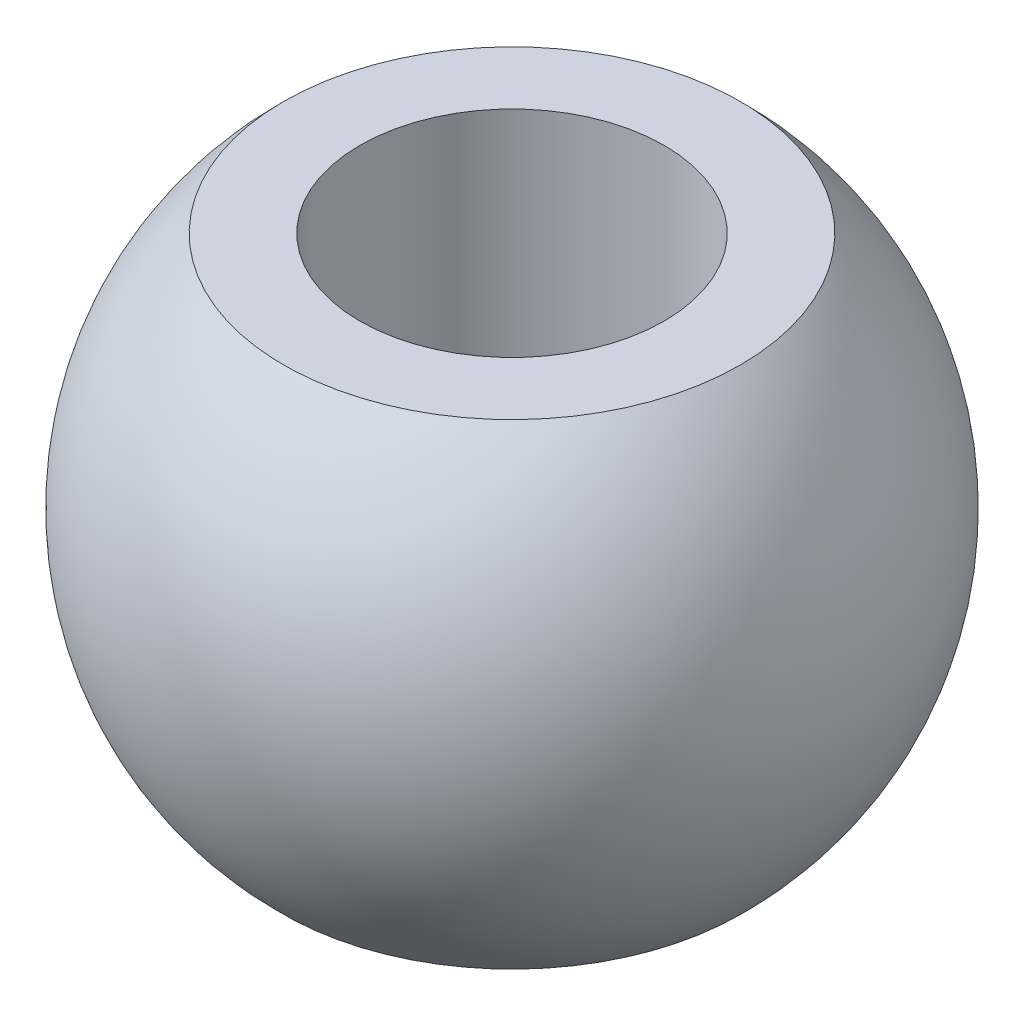
SolidWorks part; units mm, degrees
ref_plane "前视基准面" through (0, 0, 0) normal (0, 0, 1) x (1, 0, 0)
ref_plane "上视基准面" through (0, 0, 0) normal (0, 1, 0) x (1, 0, 0)
ref_plane "右视基准面" through (0, 0, 0) normal (1, 0, 0) x (0, 0, -1)
sketch "草图1" plane through (0, 0, 0) normal (0, 0, 1) x (1, 0, 0)
  line L0 (0, 7.8493) -> (0, -7.766) construction
  line L1 (0, 4.6904) -> (4.5, 4.6904)
  line L2 (-8.4205, 0) -> (8.4954, 0) construction
  line L3 (0, -4.6904) -> (4.5, -4.6904)
  line L4 (0, 4.6904) -> (0, -4.6904)
  arc A0 (-4.5, 4.6904) -> (-4.5, -4.6904) centre (0, 0) ccw construction
  arc A1 (4.5, -4.6904) -> (4.5, 4.6904) centre (0, 0) ccw
  dimension "D1" = 13
  dimension "D2" = 9
  dimension "D3" = 4.5
  dimension "D4" = 4.5
revolve "旋转2" add sketch "草图1" angle 360 about L4
sketch "草图2" plane through (0, 4.6904, 0) normal (0, 1, 0) x (1, 0, 0)
  circle A0 centre (0, 0) radius 3
  dimension "D1" = 6
extrude "切除-拉伸1" cut sketch "草图2" against normal through all
